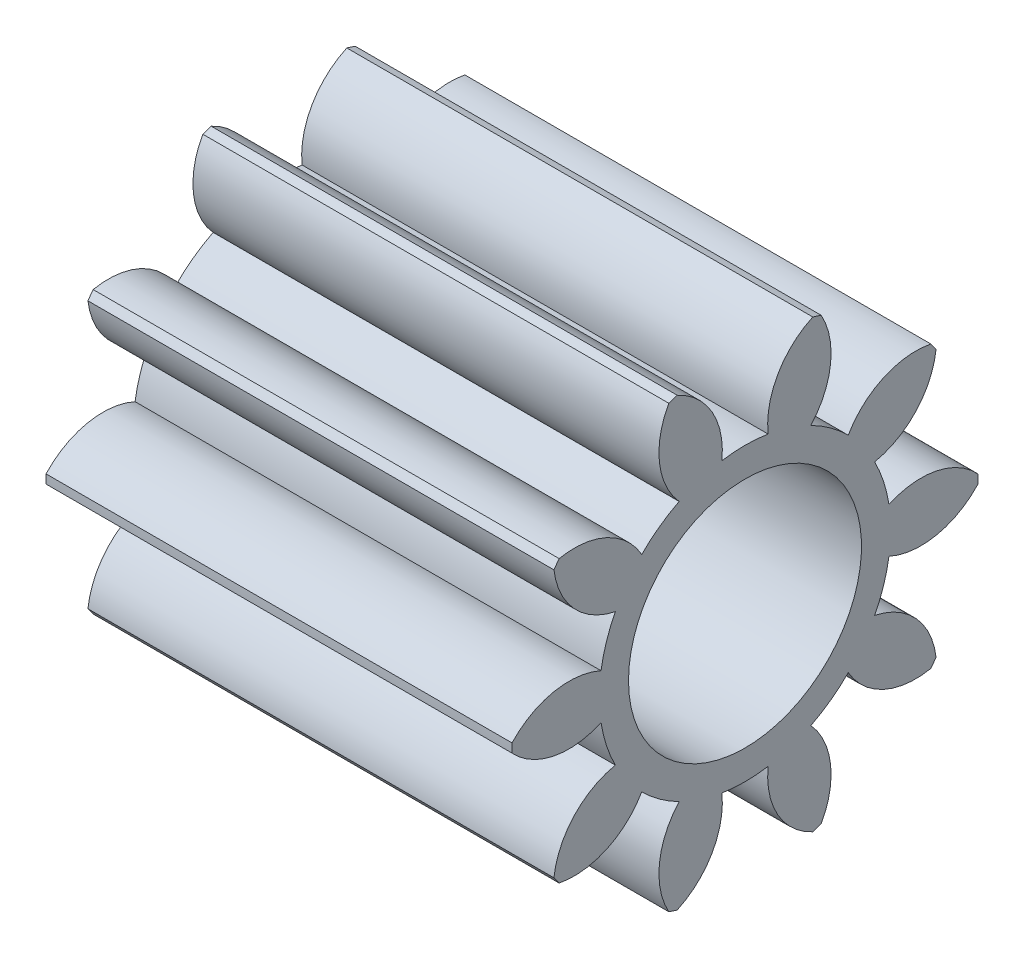
SolidWorks part; units mm, degrees
ref_plane "Plane1" through (0, 0, 0) normal (0, 0, 1) x (1, 0, 0)
ref_plane "Plane2" through (0, 0, 0) normal (0, 1, 0) x (1, 0, 0)
ref_plane "Plane3" through (0, 0, 0) normal (1, 0, 0) x (0, 0, -1)
other "Configuration Table"
sketch "HoldingSke" plane through (0, 0, 0) normal (0, 1, 0) x (1, 0, 0)
  line L0 (0, 0) -> (600.3388, -105.8559)
  line L1 (-15, 0) -> (100, 0) construction
  line L2 (0, 0) -> (-2.1039, 2.3779)
  line L3 (0, 0) -> (-11.863, 4.5341)
  line L4 (0, 0) -> (8.5048, 1.4996)
  line L5 (0, 0) -> (-47.5972, -17.7524)
  line L6 (0, 0) -> (-10.5278, -7.1032)
  line L7 (-2.1039, 2.3779) -> (8.8308, 51.9871)
  line L8 (-76.2, 54.61) -> (-69.596, 54.61)
  line L9 (-71.009, 38.7566) -> (-53.1078, 45.2721)
  line L10 (-76.2, 71.12) -> (104.1128, 71.12)
  line L11 (0, 0) -> (-12.7, 0)
  line L12 (-76.2, 101.6) -> (-76.1573, 101.6)
  line L13 (24.9733, 27.94) -> (52.9518, 28.4284)
  line L14 (24.9733, 27.94) -> (25.0241, 27.9398)
  line L15 (24.9733, 27.94) -> (100.4021, 29.52)
  circle A0 centre (0, 0) radius 3.175
  circle A1 centre (0, 0) radius 3.9709
  circle A2 centre (0, 0) radius 38.1
  circle A3 centre (0, 0) radius 3.175
  dimension "MHD" = 7.9417
  dimension "Hub_dia" = 76.2
  dimension "Bore" = 6.35
  dimension "MBD" = 6.35
  dimension "Num_teeth" = 10
  dimension "Pitch" = 609.6
  dimension "Overall_len" = 50.8
  dimension "Show_teeth" = 10
  dimension "Thickness" = 12.7
  dimension "OAL" = 50.8001
  dimension "T_dim" = 6.604
  dimension "Ap" = 20
  dimension "H" = 19.05
  dimension "Pitch_radius" = 180.3128
  dimension "Width" = 12.7
  dimension "Backlash" = 0.0427
  dimension "Addendum_fac" = 1
  dimension "Dedendum_fac" = 1.2
  dimension "Clearance_fac" = 0.2
  dimension "Dedendum_add" = 0.0508
sketch "BasProSke" plane through (0, 0, 0) normal (0, 1, 0) x (1, 0, 0)
  line L0 (-10, 0) -> (60, 0) construction
  line L1 (0, 0) -> (0, 6.35)
  line L2 (0, 0) -> (12.7, 0)
  line L3 (12.7, 0) -> (12.7, 6.35)
  line L4 (12.7, 6.35) -> (0, 6.35)
  dimension "Thickness" = 12.7
  dimension "Diameter" = 12.7
revolve "Base-Revolve" add sketch "BasProSke" angle 360 about L0
sketch "TooCutSke" plane through (0, 0, 0) normal (1, 0, 0) x (0, 0, -1)
  line L1 (0, 0) -> (0, 107) construction
  line L2 (0, 0) -> (-0.9023, 5.2142) construction
  line L3 (0, 0) -> (-3.2371, 9.9629) construction
  line L4 (-0.9023, 5.2142) -> (-1.6186, 4.9814) construction
  arc A0 (0.6302, 3.9205) -> (-0.6302, 3.9205) centre (0, 0) ccw
  arc A1 (1.8823, 6.0912) -> (-1.8823, 6.0912) centre (0, 0) ccw
  circle A2 centre (0, 0) radius 5.2917 construction
  circle A3 centre (0, 0) radius 4.9725 construction
  arc A4 (-0.6302, 3.9205) -> (-1.8823, 6.0912) centre (-2.734, 4.1535) ccw
  arc A5 (1.8823, 6.0912) -> (0.6302, 3.9205) centre (2.734, 4.1535) ccw
  dimension "Root_dia" = 7.9417
  dimension "Overcut_dia" = 12.7508
  dimension "Pitch_dia" = 10.5833
  dimension "Base_dia" = 9.9451
  dimension "Flank_rad" = 2.1167
  dimension "Half_ang" = 18
  dimension "Half_CT" = 0.7531
extrude "ToothCut" cut sketch "TooCutSke" along normal through all
fillet "Breaks" [suppressed] radius 0.0212
fillet "RootFillets" [suppressed] radius 0.2625
pattern_circular "TeethCuts" count 10 every 36 about axis through (-10, 0, 0) along (1, 0, 0) of "ToothCut", "RootFillets", "Breaks"
sketch "HubNeaOneSke" plane through (0, 0, 0) normal (-1, 0, 0) x (0, 0, 1)
  circle A0 centre (0, 0) radius 3.9709
  dimension "Diameter" = 7.9417
extrude "HubNearOne" [suppressed] add sketch "HubNeaOneSke" along normal blind 38.1001
sketch "HubNeaBotSke" plane through (0, 0, 0) normal (-1, 0, 0) x (0, 0, 1)
  circle A0 centre (0, 0) radius 3.9709
  dimension "Diameter" = 7.9417
extrude "HubNearBoth" [suppressed] add sketch "HubNeaBotSke" along normal blind 19.05
ref_plane "FarPln" through (12.7, 0, 0) normal (1, 0, 0) x (0, 0, -1)
sketch "HubFarSke" plane through (12.7, 0, 0) normal (1, 0, 0) x (0, 0, -1)
  circle A0 centre (0, 0) radius 3.9709
  dimension "Diameter" = 7.9417
extrude "HubFar" [suppressed] add sketch "HubFarSke" along normal blind 19.05
sketch "BorSke" plane through (0, 0, 0) normal (1, 0, 0) x (0, 0, -1)
  circle A0 centre (0, 0) radius 3.175
  dimension "Diameter" = 6.35
extrude "Bore" cut sketch "BorSke" along normal mid plane 101.6001
sketch "KeySke" plane through (0, 0, 0) normal (1, 0, 0) x (0, 0, -1)
  line L0 (-0.127, 0) -> (-0.127, 3.429)
  line L1 (-0.127, 3.429) -> (0.127, 3.429)
  line L2 (0.127, 3.429) -> (0.127, 0)
  line L3 (0, 0) -> (0, 34) construction
  line L4 (-0.127, 0) -> (0.127, 0)
  dimension "Offset" = 3.429
  dimension "Width" = 0.254
extrude "Keyway" [suppressed] cut sketch "KeySke" along normal mid plane 101.6001
pattern_circular "Keyway2" [suppressed] count 2 every 90 about axis through (-10, 0, 0) along (1, 0, 0)
equation "' \"Pitch@HoldingSke\" = 4"
equation "' \"Num_teeth@HoldingSke\" = 12"
equation "' \"Ap@HoldingSke\" =  20"
equation "' \"Ap@HoldingSke\" = 20"
equation "' \"Width@HoldingSke\" = 0.5"
equation "' \"Hub_dia@HoldingSke\"= 1"
equation "' \"Hub_dia@HoldingSke\" = 1"
equation "' \"Overall_len@HoldingSke\" = 1.0"
equation "' \"Bore@HoldingSke\" = 0.75"
equation "' \"T_dim@HoldingSke\" = 0.85"
equation "' \"Width@KeySke\" = 0.25"
equation "' \"Show_teeth@HoldingSke\" = 13"
equation "' \"Backlash@HoldingSke\" = 0.009"
equation "' \"Addendum_fac@HoldingSke\" = 1.0"
equation "' \"Dedendum_fac@HoldingSke\" = 1.25"
equation "' \"Dedendum_add@HoldingSke\" = 0.00005"
equation "' \"Clearance_fac@HoldingSke\" = 0.25"
equation "' \"Pitch@HoldingSke\" = 0.5"
equation "' \"Num_teeth@HoldingSke\" = 23"
equation "' \"Show_teeth@HoldingSke\" = 23"
equation "' \"Backlash@HoldingSke\" = 0.0375"
equation "\"Overcut_dia@TooCutSke\" = (\"Num_teeth@HoldingSke\" + 2 * \"Addendum_fac@HoldingSke\") / \"Pitch@HoldingSke\" + 0.002"
equation "\"Pitch_dia@TooCutSke\" = \"Num_teeth@HoldingSke\" / \"Pitch@HoldingSke\""
equation "\"Base_dia@TooCutSke\" = \"Num_teeth@HoldingSke\" / \"Pitch@HoldingSke\" * cos((\"Ap@HoldingSke\"  * 3.14159265 / 180))"
equation "\"Root_dia@TooCutSke\" = (\"Num_teeth@HoldingSke\" + 2) / \"Pitch@HoldingSke\" - 2 * (\"Addendum_fac@HoldingSke\" + \"Dedendum_fac@HoldingSke\") / \"Pitch@HoldingSke\" - \"Dedendum_add@HoldingSke\" * 2"
equation "\"Half_ang@TooCutSke\" = 180 / \"Num_teeth@HoldingSke\""
equation "\"Half_CT@TooCutSke\" = \"Num_teeth@HoldingSke\" / \"Pitch@HoldingSke\" * sin((3.14159265 / 2 / \"Num_teeth@HoldingSke\")) / 2 - 7 * \"Backlash@HoldingSke\" / 4"
equation "\"Flank_rad@TooCutSke\" = \"Num_teeth@HoldingSke\" / \"Pitch@HoldingSke\" / 5"
equation "\"Radius@RootFillets\" = \"Clearance_fac@HoldingSke\" / \"Pitch@HoldingSke\" + \"Dedendum_add@HoldingSke\""
equation "\"Break_rad@Breaks\" = 0.02 / \"Pitch@HoldingSke\""
equation "\"Thickness@HoldingSke\" = \"Width@HoldingSke\""
equation "\"OAL@HoldingSke\" = \"Thickness@HoldingSke\""
equation "\"MHD@HoldingSke\" = (\"Num_teeth@HoldingSke\" + 2) / \"Pitch@HoldingSke\" - 2 * (\"Addendum_fac@HoldingSke\" + \"Dedendum_fac@HoldingSke\")  / \"Pitch@HoldingSke\" - \"Dedendum_add@HoldingSke\" * 2"
equation "\"MBD@HoldingSke\" = (\"Num_teeth@HoldingSke\" + 2) / \"Pitch@HoldingSke\" - 2 * (\"Addendum_fac@HoldingSke\" + \"Dedendum_fac@HoldingSke\")  / \"Pitch@HoldingSke\" - \"Dedendum_add@HoldingSke\" * 2 - 0.002"
equation "\"MHD@HoldingSke\" = ((sgn( \"MHD@HoldingSke\" - \"Hub_dia@HoldingSke\" )-1)*( \"MHD@HoldingSke\" - \"Hub_dia@HoldingSke\" ))/-2+ \"Hub_dia@HoldingSke\""
equation "\"MBD@HoldingSke\" = ((sgn( \"MBD@HoldingSke\" - \"Bore@HoldingSke\" )-1)*( \"MBD@HoldingSke\" - \"Bore@HoldingSke\" ))/-2+ \"Bore@HoldingSke\""
equation "\"OAL@HoldingSke\" = ((sgn( \"OAL@HoldingSke\" - \"Overall_len@HoldingSke\" )+1)*( \"OAL@HoldingSke\" - \"Overall_len@HoldingSke\" ))/2 + \"Overall_len@HoldingSke\" + 0.000002"
equation "\"Num_teeth@TeethCuts\" = int( \"Show_teeth@HoldingSke\" ) + 1"
equation "\"Num_teeth@TeethCuts\" = ((sgn( \"Num_teeth@TeethCuts\" - \"Num_teeth@HoldingSke\" )-1)*( \"Num_teeth@TeethCuts\" - \"Num_teeth@HoldingSke\" ))/-2+ \"Num_teeth@HoldingSke\""
equation "\"Num_teeth@TeethCuts\" = ((sgn( \"Num_teeth@TeethCuts\" - 2.0)+1)*( \"Num_teeth@TeethCuts\" - 2.0))/2 +2.0"
equation "\"Angle@TeethCuts\" = 360.0 / \"Num_teeth@HoldingSke\""
equation "\"Diameter@BasProSke\" = (\"Num_teeth@HoldingSke\" + 2 * \"Addendum_fac@HoldingSke\") / \"Pitch@HoldingSke\""
equation "\"Thickness@BasProSke\"  = \"Thickness@HoldingSke\""
equation "' \"Fillet_rad@BasProSke\" =  \"Thickness@HoldingSke\" * 0.05"
equation "' \"Fillet_rad@BasProSke\" = \"Thickness@HoldingSke\" * 0.05"
equation "\"MHD@HoldingSke\" = ((sgn( \"MHD@HoldingSke\" - \"Root_dia@TooCutSke\" )-1)*( \"MHD@HoldingSke\" - \"Root_dia@TooCutSke\" ))/-2+ \"Root_dia@TooCutSke\""
equation "\"Diameter@HubNeaOneSke\" = \"MHD@HoldingSke\""
equation "\"Length@HubNearOne\" = \"OAL@HoldingSke\" - \"Thickness@BasProSke\""
equation "\"Diameter@HubNeaBotSke\" = \"MHD@HoldingSke\""
equation "\"Length@HubNearBoth\" = ( \"OAL@HoldingSke\" - \"Thickness@BasProSke\" ) / 2.0"
equation "\"Thickness@FarPln\" = \"Thickness@BasProSke\""
equation "\"Diameter@HubFarSke\" = \"MHD@HoldingSke\""
equation "\"Length@HubFar\" = ( \"OAL@HoldingSke\" - \"Thickness@BasProSke\" ) / 2.0"
equation "\"Diameter@BorSke\" = \"MBD@HoldingSke\""
equation "\"D1@Bore\" = \"OAL@HoldingSke\" * 2.0"
equation "\"D1@Keyway\" = \"OAL@HoldingSke\" * 2.0"
equation "\"Offset@KeySke\" = \"T_dim@HoldingSke\" - \"MBD@HoldingSke\" / 2.0"
